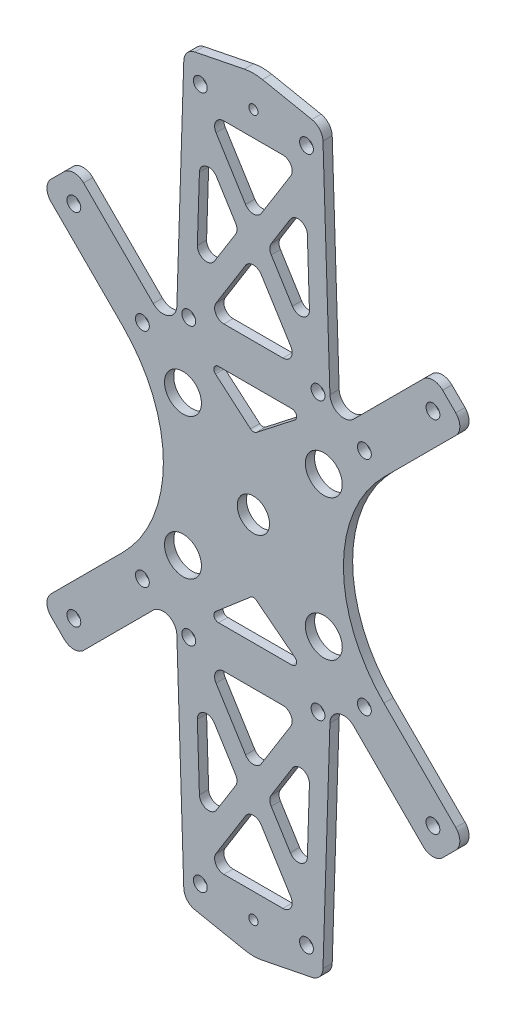
SolidWorks part; units mm, degrees
ref_plane "Alzado" through (0, 0, 0) normal (0, 0, 1) x (1, 0, 0)
ref_plane "Planta" through (0, 0, 0) normal (0, 1, 0) x (1, 0, 0)
ref_plane "Vista lateral" through (0, 0, 0) normal (1, 0, 0) x (0, 0, -1)
sketch "Croquis1" plane through (0, 0, 0) normal (0, 0, 1) x (1, 0, 0)
  line L0 (0, 0) -> (27.8544, 27.8544) construction
  line L1 (0, 0) -> (-42.4264, 42.4264) construction
  line L2 (0, 0) -> (0, 42.4264) construction
  line L3 (15.25, -15.25) -> (-15.25, -15.25) construction
  line L4 (15.25, -15.25) -> (15.25, 15.25) construction
  line L5 (15.25, 15.25) -> (-15.25, 15.25) construction
  line L6 (-15.25, -15.25) -> (-15.25, 15.25) construction
  line L7 (15.25, -15.25) -> (-15.25, 15.25) construction
  line L8 (15.25, 15.25) -> (-15.25, -15.25) construction
  line L9 (0, 42.4264) -> (-20, 42.4264) construction
  line L10 (-42.4264, 42.4264) -> (-38.8909, 45.9619)
  line L11 (-38.8909, 45.9619) -> (-31.0962, 38.1673)
  line L13 (-42.4264, 42.4264) -> (-45.9619, 38.8909)
  line L14 (-45.9619, 38.8909) -> (-38.1673, 31.0962)
  line L16 (38.8909, 45.9619) -> (31.0962, 38.1673)
  line L17 (42.4264, 42.4264) -> (38.8909, 45.9619)
  line L18 (42.4264, 42.4264) -> (45.9619, 38.8909)
  line L19 (-45.9619, -38.8909) -> (-38.1673, -31.0962)
  line L20 (0, 0) -> (-15.25, 0) construction
  line L21 (45.9619, 38.8909) -> (38.1673, 31.0962)
  line L22 (42.4264, -42.4264) -> (45.9619, -38.8909)
  line L23 (42.4264, -42.4264) -> (38.8909, -45.9619)
  line L24 (38.8909, -45.9619) -> (31.0962, -38.1673)
  line L27 (-38.8909, -45.9619) -> (-31.0962, -38.1673)
  line L28 (-42.4264, -42.4264) -> (-38.8909, -45.9619)
  line L29 (-42.4264, -42.4264) -> (-45.9619, -38.8909)
  line L30 (45.9619, -38.8909) -> (38.1673, -31.0962)
  line L31 (-15, 80) -> (15, 80) construction
  line L32 (0, -15.25) -> (0, -80) construction
  line L36 (-15, -80) -> (15, -80) construction
  line L105 (0, -80) -> (0, -83) construction
  line L106 (-15, -80) -> (0, -83)
  line L127 (15, -80) -> (0, -83)
  line L131 (0, 80) -> (0, 83) construction
  line L132 (-15, 80) -> (15, 80) construction
  line L136 (15, 80) -> (0, 83)
  line L157 (-15, 80) -> (0, 83)
  line L160 (-14, 30) -> (-17.8891, 33.8891) construction
  line L161 (-31.0962, 38.1673) -> (-21.6991, 28.7702)
  line L162 (-16.5793, 30.7953) -> (-15, 80)
  line L163 (16.5793, 30.7953) -> (15, 80)
  line L164 (31.0962, 38.1673) -> (21.6991, 28.7702)
  line L165 (31.0962, -38.1673) -> (21.6991, -28.7702)
  line L166 (16.5793, -30.7953) -> (15, -80)
  line L167 (-16.5793, -30.7953) -> (-15, -80)
  line L168 (-31.0962, -38.1673) -> (-21.6991, -28.7702)
  line L215 (-0.621, -15.7817) -> (-8.2129, -22.282)
  line L216 (-7.5625, -24.0416) -> (8.3607, -24.0416)
  line L217 (8.9758, -22.2532) -> (0.6445, -15.7529)
  line L218 (-7.5625, 24.0416) -> (8.3607, 24.0416)
  line L219 (8.9758, 22.2532) -> (0.6445, 15.7529)
  line L220 (-0.621, 15.7817) -> (-8.2129, 22.282)
  line L221 (-38.1673, 31.0962) -> (-28.2843, 21.2132)
  line L222 (-28.2843, -21.2132) -> (-38.1673, -31.0962)
  line L223 (28.2843, -21.2132) -> (38.1673, -31.0962)
  line L224 (38.1673, 31.0962) -> (28.2843, 21.2132)
  line L225 (0, -47.625) -> (0, -51.625) construction
  line L226 (0, -51.625) -> (15.9108, -51.625) construction
  line L232 (-10, -70.669) -> (10, -70.669)
  line L233 (10, -70.669) -> (0, -54.625)
  line L234 (0, -54.625) -> (-10, -70.669)
  line L235 (0, -48.625) -> (-10, -32.581)
  line L236 (10, -32.581) -> (0, -48.625)
  line L237 (-10, -32.581) -> (10, -32.581)
  line L238 (0, -51.625) -> (-15.8944, -52.1352) construction
  line L239 (-12.3776, -37.0146) -> (-11.4794, -65.0001)
  line L240 (-12.3776, -37.0146) -> (-3.207, -51.7279)
  line L241 (-3.207, -51.7279) -> (-11.4794, -65.0001)
  line L242 (3.207, -51.7279) -> (11.4794, -65.0001)
  line L243 (12.3776, -37.0146) -> (3.207, -51.7279)
  line L244 (12.3776, -37.0146) -> (11.4794, -65.0001)
  line L245 (0, 51.625) -> (-15.8944, 52.1352) construction
  line L246 (0, 51.625) -> (15.9108, 51.625) construction
  line L247 (0, 47.625) -> (0, 51.625) construction
  line L248 (12.3776, 37.0146) -> (11.4794, 65.0001)
  line L249 (12.3776, 37.0146) -> (3.207, 51.7279)
  line L250 (3.207, 51.7279) -> (11.4794, 65.0001)
  line L251 (-3.207, 51.7279) -> (-11.4794, 65.0001)
  line L252 (-12.3776, 37.0146) -> (-3.207, 51.7279)
  line L253 (-12.3776, 37.0146) -> (-11.4794, 65.0001)
  line L254 (-10, 32.581) -> (10, 32.581)
  line L255 (10, 32.581) -> (0, 48.625)
  line L256 (0, 48.625) -> (-10, 32.581)
  line L257 (0, 54.625) -> (-10, 70.669)
  line L258 (10, 70.669) -> (0, 54.625)
  line L259 (-10, 70.669) -> (10, 70.669)
  circle A0 centre (-15.25, 15.25) radius 4
  circle A1 centre (-24.0416, 24.0416) radius 1.5
  circle A2 centre (-38.8909, 38.8909) radius 1.5
  circle A5 centre (38.8909, 38.8909) radius 1.5
  circle A6 centre (24.0416, 24.0416) radius 1.5
  circle A7 centre (15.25, 15.25) radius 4
  circle A8 centre (15.25, -15.25) radius 4
  circle A9 centre (24.0416, -24.0416) radius 1.5
  circle A10 centre (38.8909, -38.8909) radius 1.5
  circle A12 centre (-15.25, -15.25) radius 4
  circle A13 centre (-24.0416, -24.0416) radius 1.5
  circle A14 centre (-38.8909, -38.8909) radius 1.5
  circle A18 centre (0, 0) radius 3.5
  circle A19 centre (-11.5, -75) radius 1.5
  circle A21 centre (-14, 30) radius 1.5
  circle A111 centre (11.5, -75) radius 1.5
  circle A112 centre (11.5, 75) radius 1.5
  circle A137 centre (-11.5, 75) radius 1.5
  arc A138 (-21.6991, 28.7702) -> (-16.5793, 30.7953) centre (-19.5778, 30.8915) ccw
  arc A139 (21.6991, 28.7702) -> (16.5793, 30.7953) centre (19.5778, 30.8915) cw
  arc A140 (21.6991, -28.7702) -> (16.5793, -30.7953) centre (19.5778, -30.8915) ccw
  arc A141 (-21.6991, -28.7702) -> (-16.5793, -30.7953) centre (-19.5778, -30.8915) cw
  circle A142 centre (14, 30) radius 1.5
  circle A143 centre (14, -30) radius 1.5
  circle A144 centre (-14, -30) radius 1.5
  arc A191 (8.3607, -24.0416) -> (8.9758, -22.2532) centre (8.3607, -23.0416) ccw
  arc A192 (0.6445, -15.7529) -> (-0.621, -15.7817) centre (0.0294, -16.5413) ccw
  arc A193 (-8.2129, -22.282) -> (-7.5625, -24.0416) centre (-7.5625, -23.0416) ccw
  arc A194 (8.3607, 24.0416) -> (8.9758, 22.2532) centre (8.3607, 23.0416) cw
  arc A195 (0.6445, 15.7529) -> (-0.621, 15.7817) centre (0.0294, 16.5413) cw
  arc A196 (-8.2129, 22.282) -> (-7.5625, 24.0416) centre (-7.5625, 23.0416) cw
  arc A197 (-28.2843, 21.2132) -> (-28.2843, -21.2132) centre (-49.4975, 0) cw
  arc A198 (28.2843, 21.2132) -> (28.2843, -21.2132) centre (49.4975, 0) ccw
  circle A199 centre (0, 76) radius 1
  circle A200 centre (0, -76) radius 1
  point P35 (-34.9935, 42.0646)
  point P37 (44.1942, 40.6586)
  point P45 (44.1942, -40.6586)
  point P61 (-34.9935, -42.0646)
  point P70 (0, 80)
  point P260 (-7.0711, 0)
  dimension "D2" = 8
  dimension "D4" = 5
  dimension "D8" = 14.75
  dimension "D10" = 3
  dimension "D11" = 3
  dimension "D13" = 11.5
  dimension "D15" = 3
  dimension "D16" = 14
  dimension "D18" = 3
  dimension "D24" = 3
  dimension "D26" = 1
  dimension "D27" = 7
  dimension "D28" = 30
  dimension "D29" = 7
  dimension "D1" = 30.5
  dimension "D3" = 60
  dimension "D5" = 21
  dimension "D6" = 15
  dimension "D7" = 5
  dimension "D9" = 5
  dimension "D12" = 80
  dimension "D14" = 5
  dimension "D17" = 10
  dimension "D19" = 28.375
  dimension "D20" = 3
  dimension "D21" = 4
  dimension "D22" = 15
  dimension "D25" = 13
  dimension "D23" = 5.5
  dimension "D30" = 10
  dimension "D31" = 0
extrude "Saliente-Extruir1" add sketch "Croquis1" along normal blind 2
fillet "Redondeo1" radius 3 12 edges at (45.9619, -38.8909, 1) (38.8909, -45.9619, 1) (-45.9619, -38.8909, 1) (-38.8909, -45.9619, 1) (45.9619, 38.8909, 1) (38.8909, 45.9619, 1) (-38.8909, 45.9619, 1) (-45.9619, 38.8909, 1) (15, 80, 1) (-15, 80, 1) (15, -80, 1) (-15, -80, 1)
fillet "Redondeo2" radius 10 2 edges at (0, -83, 1) (0, 83, 1)
fillet "Redondeo3" radius 2 24 edges at (10, 70.669, 1) (-10, 70.669, 1) (12.3776, 37.0146, 1) (10, 32.581, 1) (-10, 32.581, 1) (-12.3776, 37.0146, 1) (-11.4794, 65.0001, 1) (0, 54.625, 1) (3.207, 51.7279, 1) (0, 48.625, 1) (-3.207, 51.7279, 1) (11.4794, -65.0001, 1) (3.207, -51.7279, 1) (12.3776, -37.0146, 1) (10, -32.581, 1) (0, -48.625, 1) (-10, -32.581, 1) (10, -70.669, 1) (0, -54.625, 1) (-10, -70.669, 1) (-11.4794, -65.0001, 1) (-3.207, -51.7279, 1) (-12.3776, -37.0146, 1) (11.4794, 65.0001, 1)
sketch "Croquis2" plane through (0, 0, 2) normal (0, 0, 1) x (1, 0, 0)
  line L0 (0, 82.802) -> (0, 32.581) construction
  line L2 (-11.5, 67.669) -> (-11.5, 64.669)
  line L4 (-9.5, 67.669) -> (-9.5, 64.669)
  line L5 (-6.3967, 32.581) -> (6.3967, 32.581) construction
  line L6 (6.3967, 70.669) -> (-6.3967, 70.669) construction
  line L7 (9.5, 67.669) -> (9.5, 64.669)
  line L8 (11.5, 67.669) -> (11.5, 64.669)
  line L9 (9.5, 40.669) -> (9.5, 37.669)
  line L10 (11.5, 40.669) -> (11.5, 37.669)
  line L11 (-11.5, 40.669) -> (-11.5, 37.669)
  line L12 (-9.5, 40.669) -> (-9.5, 37.669)
  line L13 (-19.4975, 0) -> (19.4975, 0) construction
  line L14 (0, -82.802) -> (0, -32.581) construction
  line L15 (-9.5, -40.669) -> (-9.5, -37.669)
  line L16 (-11.5, -40.669) -> (-11.5, -37.669)
  line L17 (11.5, -40.669) -> (11.5, -37.669)
  line L18 (9.5, -40.669) -> (9.5, -37.669)
  line L19 (11.5, -67.669) -> (11.5, -64.669)
  line L20 (9.5, -67.669) -> (9.5, -64.669)
  line L21 (-9.5, -67.669) -> (-9.5, -64.669)
  line L22 (-11.5, -67.669) -> (-11.5, -64.669)
  arc A0 (1.9612, 82.6078) -> (-1.9612, 82.6078) centre (0, 72.802) ccw construction
  arc A1 (-11.5, 67.669) -> (-9.5, 67.669) centre (-10.5, 67.669) cw
  arc A2 (-11.5, 64.669) -> (-9.5, 64.669) centre (-10.5, 64.669) ccw
  arc A3 (9.5, 67.669) -> (11.5, 67.669) centre (10.5, 67.669) cw
  arc A4 (9.5, 64.669) -> (11.5, 64.669) centre (10.5, 64.669) ccw
  arc A5 (9.5, 40.669) -> (11.5, 40.669) centre (10.5, 40.669) cw
  arc A6 (9.5, 37.669) -> (11.5, 37.669) centre (10.5, 37.669) ccw
  arc A7 (-11.5, 40.669) -> (-9.5, 40.669) centre (-10.5, 40.669) cw
  arc A8 (-11.5, 37.669) -> (-9.5, 37.669) centre (-10.5, 37.669) ccw
  arc A9 (-28.2843, -21.2132) -> (-28.2843, 21.2132) centre (-49.4975, 0) ccw construction
  arc A10 (28.2843, 21.2132) -> (28.2843, -21.2132) centre (49.4975, 0) ccw construction
  arc A11 (-11.5, -37.669) -> (-9.5, -37.669) centre (-10.5, -37.669) cw
  arc A12 (-11.5, -40.669) -> (-9.5, -40.669) centre (-10.5, -40.669) ccw
  arc A13 (9.5, -37.669) -> (11.5, -37.669) centre (10.5, -37.669) cw
  arc A14 (9.5, -40.669) -> (11.5, -40.669) centre (10.5, -40.669) ccw
  arc A15 (9.5, -64.669) -> (11.5, -64.669) centre (10.5, -64.669) cw
  arc A16 (9.5, -67.669) -> (11.5, -67.669) centre (10.5, -67.669) ccw
  arc A17 (-11.5, -64.669) -> (-9.5, -64.669) centre (-10.5, -64.669) cw
  arc A18 (-11.5, -67.669) -> (-9.5, -67.669) centre (-10.5, -67.669) ccw
  dimension "D1" = 3
  dimension "D2" = 2
  dimension "D3" = 9.5
  dimension "D4" = 3
  dimension "D7" = 24
  dimension "D5" = 2
  dimension "D6" = 2
extrude "Cortar-Extruir1" [suppressed] cut sketch "Croquis2" against normal up to vertex
